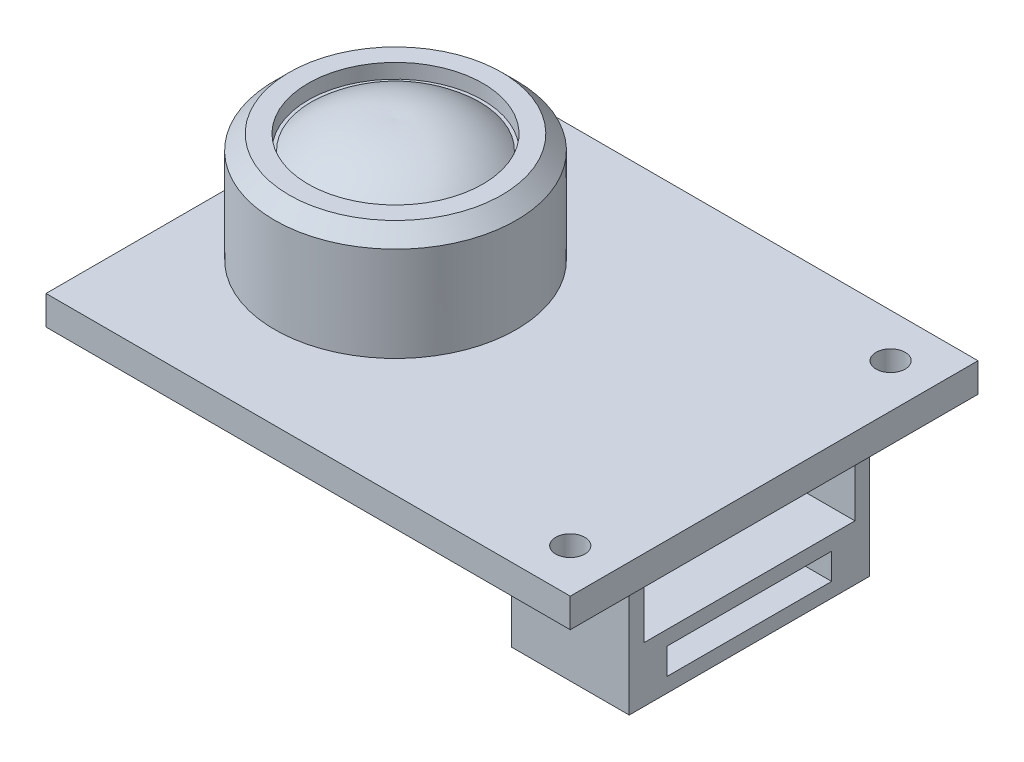
SolidWorks part; units mm, degrees
ref_plane "Front Plane" through (0, 0, 0) normal (0, 0, 1) x (1, 0, 0)
ref_plane "Top Plane" through (0, 0, 0) normal (0, 1, 0) x (1, 0, 0)
ref_plane "Right Plane" through (0, 0, 0) normal (1, 0, 0) x (0, 0, -1)
sketch "Sketch1" plane through (0, 0, 0) normal (0, 1, 0) x (1, 0, 0)
  line L1 (0, 0) -> (18, 0)
  line L2 (0, 0) -> (0, 14)
  line L3 (0, 14) -> (18, 14)
  line L4 (18, 0) -> (18, 14)
  circle A0 centre (16.5, 12.5) radius 0.5
  circle A1 centre (16.5, 1.5) radius 0.5
  dimension "D3" = 16.5
  dimension "D4" = 16.5
  dimension "D5" = 1
  dimension "D6" = 1
  dimension "D7" = 1.5
  dimension "D8" = 1.5
  dimension "D1" = 18
  dimension "D2" = 14
extrude "Boss-Extrude1" add sketch "Sketch1" along normal blind 1
sketch "Sketch2" plane through (0, 1, 0) normal (0, 1, 0) x (1, 0, 0)
  line L0 (0, 14) -> (0, 0) construction
  line L1 (18, 14) -> (0, 14) construction
  circle A0 centre (5, 7) radius 4.15
  dimension "D1" = 8.3
  dimension "D2" = 5
  dimension "D3" = 7
extrude "Boss-Extrude2" add sketch "Sketch2" along normal blind 3.75
sketch "Sketch3" plane through (0, 0, 0) normal (0, -1, 0) x (-1, 0, 0)
  line L0 (0, 0) -> (-18, 0) construction
  line L1 (-17.15, 11.125) -> (-13.1, 11.125)
  line L2 (-17.15, 11.125) -> (-17.15, 2.875)
  line L3 (-17.15, 2.875) -> (-13.1, 2.875)
  line L4 (-13.1, 11.125) -> (-13.1, 2.875)
  line L5 (-18, 0) -> (-18, 14) construction
  dimension "D1" = 8.25
  dimension "D2" = 2.875
  dimension "D3" = 4.05
  dimension "D4" = 0.85
extrude "Boss-Extrude3" add sketch "Sketch3" along normal blind 4.4
sketch "Sketch4" plane through (17.15, 0, 0) normal (1, 0, 0) x (0, 0, -1)
  line L0 (2.875, -4.4) -> (2.875, 0) construction
  line L1 (3.375, -0.5) -> (10.625, -0.5)
  line L2 (3.375, -0.5) -> (3.375, -2.5)
  line L3 (3.375, -2.5) -> (10.625, -2.5)
  line L4 (10.625, -0.5) -> (10.625, -2.5)
  line L5 (4.175, -3) -> (9.825, -3)
  line L6 (4.175, -3) -> (4.175, -3.9)
  line L7 (4.175, -3.9) -> (9.825, -3.9)
  line L8 (9.825, -3) -> (9.825, -3.9)
  line L9 (11.125, -4.4) -> (11.125, 0) construction
  line L10 (11.125, -4.4) -> (2.875, -4.4) construction
  line L11 (11.125, 0) -> (2.875, 0) construction
  dimension "D1" = 2
  dimension "D2" = 0.5
  dimension "D3" = 0.5
  dimension "D4" = 1.3
  dimension "D5" = 1.3
  dimension "D6" = 0.5
  dimension "D7" = 0.5
  dimension "D8" = 0.5
extrude "Cut-Extrude1" cut sketch "Sketch4" against normal blind 3
sketch "Sketch5" plane through (0, 4.75, 0) normal (0, 1, 0) x (1, 0, 0)
  circle A0 centre (5, 7) radius 3
  circle A1 centre (5, 7) radius 4.15 construction
  dimension "D1" = 0
  dimension "D2" = 6
extrude "Cut-Extrude2" cut sketch "Sketch5" against normal blind 0.5
chamfer "Chamfer1" distance 0.5 angle 45
ref_plane "Plane1" through (0, 0, -7) normal (0, 0, 1) x (1, 0, 0)
ref_plane "Plane2" through (5, 0, 0) normal (1, 0, 0) x (0, 0, -1)
sketch "Sketch7" plane through (0, 0, -7) normal (0, 0, 1) x (1, 0, 0)
  line L0 (4.9985, 4.2328) -> (4.9985, 5.2096)
  line L1 (4.9985, 5.2096) -> (4.9985, 4.2328)
  line L2 (4.9985, 4.2328) -> (2.0903, 4.2328)
  spline S0 degree 2 poles (2.0903, 4.2328) (3.3508, 5.3248) (4.9985, 5.2096) knots 0 0 0 1 1 1
revolve "Revolve2" add sketch "Sketch7" angle 360 about L0
